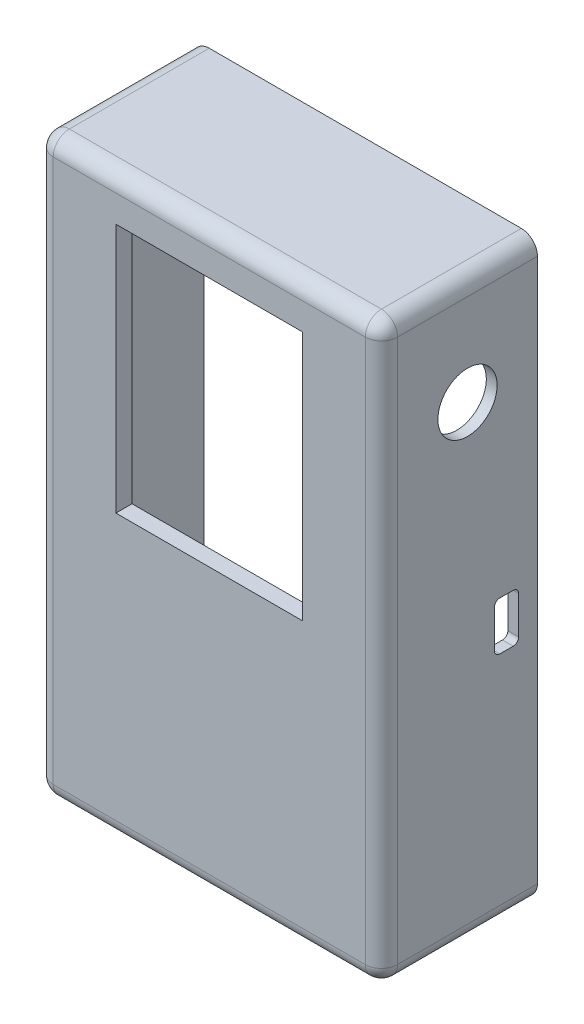
SolidWorks part; units mm, degrees
ref_plane "Front" through (0, 0, 0) normal (0, 0, 1) x (1, 0, 0)
ref_plane "Top" through (0, 0, 0) normal (0, 1, 0) x (1, 0, 0)
ref_plane "Right" through (0, 0, 0) normal (1, 0, 0) x (0, 0, -1)
sketch "Esquisse1" plane through (0, 0, 0) normal (0, 0, 1) x (1, 0, 0)
  line L1 (0, 0) -> (60, 0)
  line L2 (0, 0) -> (0, 103)
  line L3 (0, 103) -> (60, 103)
  line L4 (60, 0) -> (60, 103)
  dimension "D1" = 60
  dimension "D2" = 103
extrude "Boss.-Extru.1" add sketch "Esquisse1" along normal blind 3
sketch "Esquisse2" plane through (0, 0, 3) normal (0, 0, 1) x (1, 0, 0)
  line L0 (30, 97) -> (30, 103) construction
  line L1 (12.65, 97) -> (47.35, 97)
  line L2 (12.65, 97) -> (12.65, 50.5)
  line L3 (12.65, 50.5) -> (47.35, 50.5)
  line L4 (47.35, 97) -> (47.35, 50.5)
  line L5 (60, 103) -> (0, 103) construction
  dimension "D1" = 34.7
  dimension "D2" = 6
  dimension "D3" = 46.5
extrude "Enlèv. mat.-Extru.1" cut sketch "Esquisse2" against normal through all
sketch "Esquisse3" plane through (0, 0, 0) normal (0, 0, -1) x (-1, 0, 0)
  line L0 (-30, 101) -> (-30, 103) construction
  line L1 (-50.5, 101) -> (-9.5, 101)
  line L2 (-50.5, 101) -> (-50.5, 98.2)
  line L3 (-50.5, 98.2) -> (-9.5, 98.2)
  line L4 (-9.5, 101) -> (-9.5, 98.2)
  line L5 (-60, 103) -> (0, 103) construction
  line L6 (-47.35, 97) -> (-12.65, 97) construction
  dimension "D1" = 2.8
  dimension "D2" = 4
  dimension "D3" = 41
extrude "Enlèv. mat.-Extru.2" cut sketch "Esquisse3" against normal blind 1.8
sketch "Esquisse4" plane through (0, 0, 0) normal (0, 0, -1) x (-1, 0, 0)
  line L0 (-60, 51.5) -> (-62, 51.5) construction
  line L1 (-60, 0) -> (0, 0)
  line L2 (-60, 0) -> (-60, 103)
  line L3 (-60, 103) -> (0, 103)
  line L4 (0, 0) -> (0, 103)
  line L5 (2, 105) -> (-62, 105)
  line L6 (2, 105) -> (2, -2)
  line L7 (2, -2) -> (-62, -2)
  line L8 (-62, 105) -> (-62, -2)
  line L9 (-30, 103) -> (-30, 105) construction
  point P14 (0, 0)
  dimension "D1" = 2
  dimension "D2" = 2
extrude "Boss.-Extru.2" add sketch "Esquisse4" along normal blind 26 and the other way up to vertex (3 mm away) other way up to point (0, 103, 3)
sketch "Esquisse5" plane through (62, 0, 0) normal (1, 0, 0) x (0, 0, -1)
  line L1 (18, 50.5) -> (22.5, 50.5)
  line L2 (18, 50.5) -> (18, 41.5)
  line L3 (18, 41.5) -> (22.5, 41.5)
  line L4 (22.5, 50.5) -> (22.5, 41.5)
  line L5 (0, 50.5) -> (0, 97) construction
  line L6 (0, 50.5) -> (-3, 50.5) construction
  line L7 (26, 105) -> (26, -2) construction
  line L8 (-3, 105) -> (26, 105) construction
  circle A0 centre (13, 85) radius 5.5
  point P4 (18, 46)
  dimension "D5" = 11
  dimension "D6" = 20
  dimension "D1" = 18
  dimension "D2" = 9
  dimension "D3" = 4.5
  dimension "D4" = 13
extrude "Enlèv. mat.-Extru.3" cut sketch "Esquisse5" against normal up to next
fillet "Congé1" radius 1 4 edges at (61, 41.5, -22.5) (61, 50.5, -22.5) (61, 50.5, -18) (61, 41.5, -18)
fillet "Congé2" radius 3 8 edges at (62, -2, -11.5) (-2, -2, -11.5) (62, 105, -11.5) (-2, 105, -11.5) (62, 51.5, 3) (30, -2, 3) (-2, 51.5, 3) (30, 105, 3)
sketch "Esquisse6" plane through (0, 0, -26) normal (0, 0, -1) x (-1, 0, 0)
  line L0 (-60, 103) -> (-55, 103)
  line L1 (0, 103) -> (-60, 103) construction
  line L2 (-55, 103) -> (-55, 98)
  line L3 (-60, 103) -> (-55, 98) construction
  line L4 (-60, 98) -> (-55, 98)
  line L5 (-60, 103) -> (-60, 98)
  line L6 (-30, 103) -> (-30, 51.5) construction
  line L7 (-30, 51.5) -> (2, 51.5) construction
  line L8 (2, 1) -> (2, 102) construction
  line L9 (0, 103) -> (-5, 98) construction
  line L10 (0, 103) -> (0, 98)
  line L11 (0, 98) -> (-5, 98)
  line L12 (-5, 103) -> (-5, 98)
  line L13 (0, 103) -> (-5, 103)
  line L14 (0, 0) -> (-5, 5) construction
  line L15 (-60, 0) -> (-55, 5) construction
  line L16 (0, 0) -> (-5, 0)
  line L17 (-5, 0) -> (-5, 5)
  line L18 (0, 5) -> (-5, 5)
  line L19 (0, 0) -> (0, 5)
  line L20 (-60, 0) -> (-60, 5)
  line L21 (-60, 5) -> (-55, 5)
  line L22 (-55, 0) -> (-55, 5)
  line L23 (-60, 0) -> (-55, 0)
  point P9 (2, 51.5)
  dimension "D1" = 5
extrude "Boss.-Extru.3" add sketch "Esquisse6" against normal up to vertex (26 mm away) up to point (0, 0, 0)
fillet "Congé3" radius 4 4 edges at (5, 98, -13) (55, 98, -13) (55, 5, -13) (5, 5, -13)
sketch "Esquisse7" plane through (0, 0, -26) normal (0, 0, -1) x (-1, 0, 0)
  line L0 (-30, 103) -> (-30, 51.5) construction
  line L1 (-5, 103) -> (-55, 103) construction
  line L2 (-30, 51.5) -> (0, 51.5) construction
  line L3 (0, 5) -> (0, 98) construction
  line L4 (1.1213, 104.1213) -> (-3.8284, 99.1716) construction
  circle A0 centre (-1.3536, 101.6464) radius 1.3
  circle A1 centre (-58.6464, 101.6464) radius 1.3
  circle A2 centre (-58.6464, 1.3536) radius 1.3
  circle A3 centre (-1.3536, 1.3536) radius 1.3
  arc A5 (2, 102) -> (-1, 105) centre (-1, 102) ccw construction
  arc A6 (-5, 102) -> (-1, 98) centre (-1, 102) ccw construction
  point P16 (-1.3536, 101.6464)
  dimension "D1" = 2.6
extrude "Enlèv. mat.-Extru.4" cut sketch "Esquisse7" against normal blind 10
sketch "Esquisse8" plane through (0, -2, 0) normal (0, -1, 0) x (-1, 0, 0)
  line L0 (-14, 26) -> (-14, -3) construction
  line L4 (-59, 26) -> (-1, 26) construction
  line L5 (-1, -3) -> (-59, -3) construction
  line L6 (2, 26) -> (2, 0) construction
  circle A0 centre (-14, 11.5) radius 7
  point P2 (0, 0)
  point P5 (-50, 26)
  point P8 (0, 0)
  point P11 (-50, -3)
  dimension "D1" = 14
  dimension "D2" = 16
extrude "Enlèv. mat.-Extru.5" cut sketch "Esquisse8" against normal up to next
